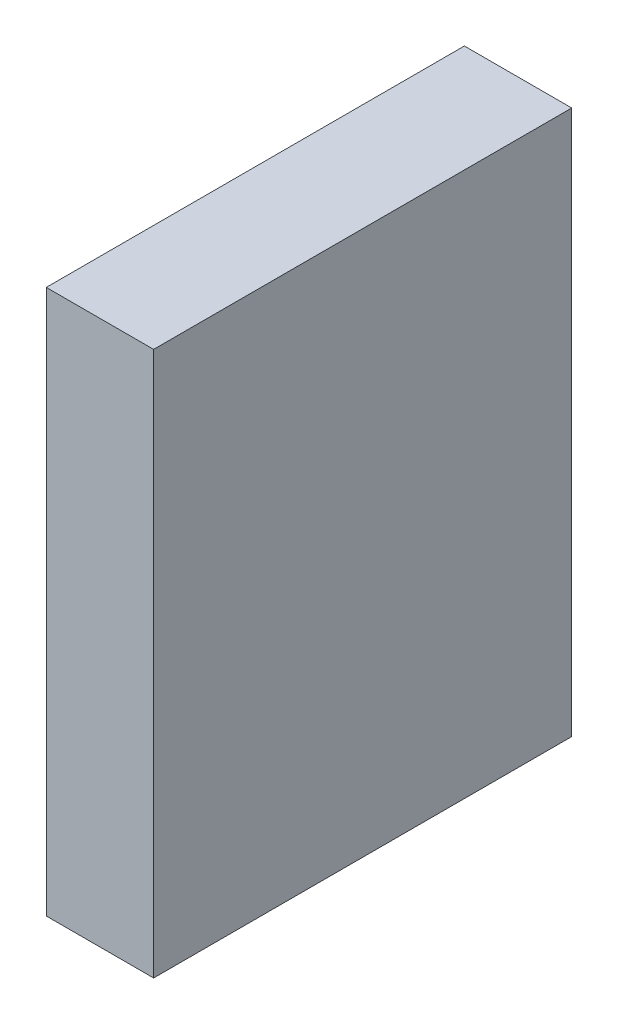
SolidWorks part; units mm, degrees
ref_plane "Front Plane" through (0, 0, 0) normal (0, 0, 1) x (1, 0, 0)
ref_plane "Top Plane" through (0, 0, 0) normal (0, 1, 0) x (1, 0, 0)
ref_plane "Right Plane" through (0, 0, 0) normal (1, 0, 0) x (0, 0, -1)
sketch "Sketch1" plane through (0, 0, 0) normal (1, 0, 0) x (0, 0, -1)
  line L1 (-10.145, -13.21) -> (10.145, -13.21)
  line L2 (-10.145, -13.21) -> (-10.145, 13.21)
  line L3 (-10.145, 13.21) -> (10.145, 13.21)
  line L4 (10.145, -13.21) -> (10.145, 13.21)
  line L5 (-10.145, -13.21) -> (10.145, 13.21) construction
  line L6 (-10.145, 13.21) -> (10.145, -13.21) construction
  point P0 (0, 0)
  dimension "D1" = 20.29
  dimension "D2" = 26.42
extrude "Boss-Extrude1" add sketch "Sketch1" along normal blind 5.21
sketch "Sketch2" plane through (0, -13.21, 0) normal (0, -1, 0) x (1, 0, 0)
  line L0 (2.605, -10.145) -> (2.605, 10.145) construction
  line L1 (5.21, -10.145) -> (0, -10.145) construction
  line L2 (5.21, 10.145) -> (0, 10.145) construction
  circle A0 centre (2.605, -7.0739) radius 0.915
  circle A1 centre (2.605, -3.2639) radius 0.865
  circle A2 centre (2.605, 8.1661) radius 0.7
  dimension "D1" = 1.83
  dimension "D2" = 1.73
  dimension "D3" = 1.4
  dimension "D5" = 11.43
  dimension "D4" = 3.81
extrude "Boss-Extrude2" [suppressed] add sketch "Sketch2" along normal blind 3
